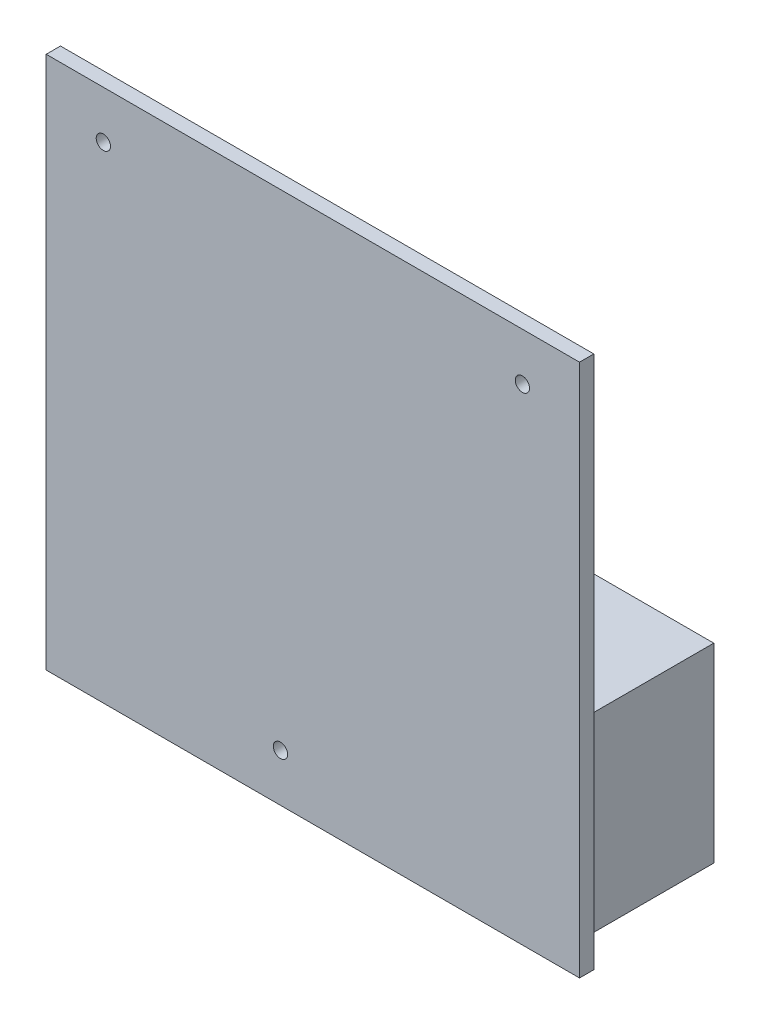
SolidWorks part; units mm, degrees
ref_plane "Alzado" through (0, 0, 0) normal (0, 0, 1) x (1, 0, 0)
ref_plane "Planta" through (0, 0, 0) normal (0, 1, 0) x (1, 0, 0)
ref_plane "Vista lateral" through (0, 0, 0) normal (1, 0, 0) x (0, 0, -1)
sketch "Croquis1" plane through (0, 0, 0) normal (0, 0, 1) x (1, 0, 0)
  line L1 (-56, -56) -> (56, -56)
  line L2 (-56, -56) -> (-56, 56)
  line L3 (-56, 56) -> (56, 56)
  line L4 (56, -56) -> (56, 56)
  line L5 (-56, -56) -> (56, 56) construction
  line L6 (-56, 56) -> (56, -56) construction
  point P0 (0, 0)
  dimension "D1" = 112
  dimension "D2" = 112
extrude "Saliente-Extruir1" add sketch "Croquis1" along normal blind 3
sketch "Croquis2" plane through (0, 0, 3) normal (0, 0, 1) x (1, 0, 0)
  line L0 (56, -56) -> (49.197, -56)
  line L1 (-56, -56) -> (56, -56) construction
  line L3 (49.197, -56) -> (-0.803, -56)
  line L4 (49.197, -56) -> (49.197, -16)
  line L5 (49.197, -16) -> (-0.803, -16)
  line L6 (-0.803, -56) -> (-0.803, -16)
  line M7 (-56, -56) -> (56, -56)
  dimension "D1" = 6.803
  dimension "D2" = 40
  dimension "D3" = 50
extrude "Saliente-Extruir2" add sketch "Croquis2" along normal blind 32 contours L6 L4 L5 M7
sketch "Croquis3" plane through (0, 0, 3) normal (0, 0, 1) x (1, 0, 0)
  line L0 (-42, -56) -> (-42, -17.5)
  line L1 (-56, -56) -> (-0.803, -56) construction
  line L2 (-52, -17.5) -> (-32, -17.5)
  line L3 (-56, 56) -> (-56, -56) construction
  line L4 (-52, -17.5) -> (-52, 17.5)
  line L5 (-52, 17.5) -> (-32, 17.5)
  line L6 (-32, 17.5) -> (-32, -17.5)
  point P7 (-42, -17.5)
  dimension "D1" = 38.5
  dimension "D2" = 20
  dimension "D3" = 4
  dimension "D4" = 35
extrude "Saliente-Extruir3" add sketch "Croquis3" along normal blind 18 contours L6 L2 L4 L5
sketch "Croquis4" plane through (0, 0, 21) normal (0, 0, 1) x (1, 0, 0)
  line L0 (-52, 15) -> (-34.5, 15)
  line L1 (-52, -17.5) -> (-52, 17.5) construction
  line L2 (-34.5, 15) -> (-34.5, -15)
  line L3 (-34.5, -15) -> (-52, -15)
  line L4 (-52, -17.5) -> (-52, 17.5) construction
  line L5 (-52, -15) -> (-52, 15)
  line L6 (-52, 17.5) -> (-32, 17.5) construction
  line L7 (-32, 17.5) -> (-32, -17.5) construction
  line L8 (-52, -17.5) -> (-32, -17.5) construction
  dimension "D1" = 2.5
  dimension "D2" = 2.5
  dimension "D3" = 2.5
extrude "Cortar-Extruir1" cut sketch "Croquis4" against normal blind 16
sketch "Croquis5" plane through (0, -17.5, 0) normal (0, -1, 0) x (1, 0, 0)
  line L0 (-52, 3) -> (-52, 11)
  line L1 (-52, 21) -> (-52, 3) construction
  line L2 (-52, 11) -> (-34.0003, 21)
  line L3 (-52, 21) -> (-32, 21) construction
  line L4 (-34.0003, 21) -> (-52, 21)
  line L5 (-52, 21) -> (-52, 11)
  line M5 (-32, 21) -> (-52, 21)
  line M6 (-52, 21) -> (-52, 3)
  dimension "D1" = 8
  dimension "D2" = 20.591
extrude "Cortar-Extruir2" cut sketch "Croquis5" against normal blind 46 contours L2 M6 M5
sketch "Croquis6" plane through (0, 0, 3) normal (0, 0, 1) x (1, 0, 0)
  line L0 (-56, 56) -> (-56, -56) construction
  line L1 (56, 56) -> (-56, 56) construction
  line L2 (-0.803, -56) -> (-0.803, -16) construction
  line L3 (-56, -56) -> (-0.803, -56) construction
  circle A0 centre (-44, 46) radius 1.5
  circle A1 centre (44, 46) radius 1.5
  circle A2 centre (-6.803, -46) radius 1.5
  dimension "D1" = 12
  dimension "D4" = 3
  dimension "D6" = 10
  dimension "D2" = 88
  dimension "D3" = 10
  dimension "D5" = 6
extrude "Cortar-Extruir3" cut sketch "Croquis6" against normal blind 46
mirror "Simetría1" about plane through (0, 0, 0) normal (0, 0, -1) of "Saliente-Extruir1", "Saliente-Extruir2", "Saliente-Extruir3", "Cortar-Extruir1", "Cortar-Extruir2", "Cortar-Extruir3"
sketch "Croquis7" plane through (56, 0, 0) normal (1, 0, 0) x (0, 0, -1)
  line L0 (3, 56) -> (0, 56)
  line L1 (-3, 56) -> (3, 56) construction
  line L2 (0, 56) -> (0, -56)
  line L3 (-3, -56) -> (3, -56) construction
  line L4 (0, -56) -> (-62.8748, -56)
  line L5 (-62.8748, -56) -> (-62.8748, 56)
  line L6 (-62.8748, 56) -> (0, 56)
  line M4 (-3, 56) -> (-3, -56)
extrude "Cortar-Extruir4" cut sketch "Croquis7" against normal blind 160 contours L6 L5 L4 M4
sketch "Croquis8" plane through (56, 0, 0) normal (1, 0, 0) x (0, 0, -1)
  line L0 (3, 56) -> (0, 56)
  line L1 (-3, 56) -> (3, 56) construction
  line L2 (0, 56) -> (0, -56)
  line L3 (-3, -56) -> (3, -56) construction
  line L4 (0, -56) -> (-11.646, -56)
  line L5 (-11.646, -56) -> (-11.646, 56)
  line L6 (-11.646, 56) -> (0, 56)
  line M1 (-3, -56) -> (3, -56)
  line M3 (3, 56) -> (-3, 56)
  line M4 (-3, 56) -> (-3, -56)
extrude "Cortar-Extruir5" cut sketch "Croquis8" against normal blind 150 contours L6 L5 L4 M4 | L2 M3 M4 M1
